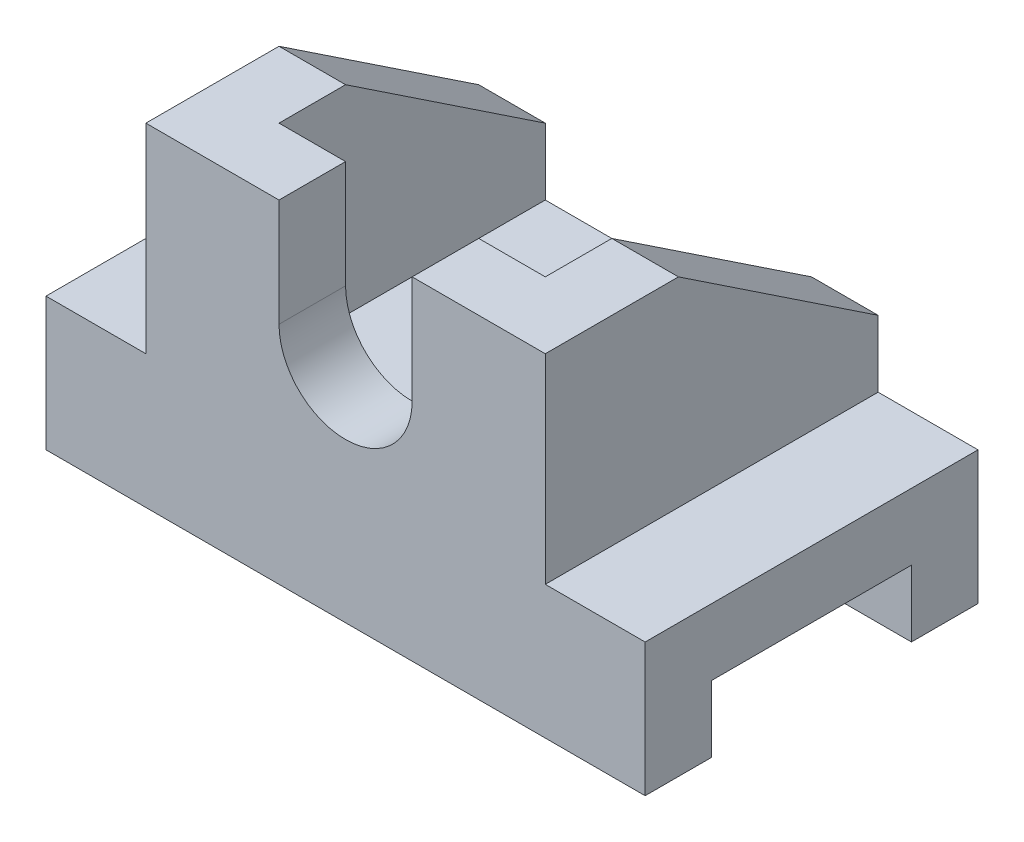
SolidWorks part; units mm, degrees
material "Nickel"
ref_plane "Front Plane" through (0, 0, 0) normal (0, 0, 1) x (1, 0, 0)
ref_plane "Top Plane" through (0, 0, 0) normal (0, 1, 0) x (1, 0, 0)
ref_plane "Right Plane" through (0, 0, 0) normal (1, 0, 0) x (0, 0, -1)
sketch "Sketch1" plane through (0, 0, 0) normal (1, 0, 0) x (0, 0, -1)
  line L0 (-14.6591, 0) -> (15.3409, 0)
  line L1 (15.3409, 0) -> (15.3409, -10)
  line L2 (15.3409, -10) -> (25.3409, -10)
  line L3 (25.3409, -10) -> (25.3409, 10)
  line L4 (25.3409, 10) -> (-24.6591, 10)
  line L5 (-24.6591, 10) -> (-24.6591, -10)
  line L6 (-24.6591, -10) -> (-14.6591, -10)
  line L7 (-14.6591, -10) -> (-14.6591, 0)
  dimension "D1" = 50
  dimension "D2" = 10
  dimension "D3" = 10
  dimension "D4" = 20
extrude "Boss-Extrude1" add sketch "Sketch1" along normal mid plane 90
sketch "Sketch2" plane through (0, 0, 24.6591) normal (0, 0, 1) x (1, 0, 0)
  line L0 (-30, 10) -> (-30, 40)
  line L1 (-30, 40) -> (30, 40)
  line L2 (30, 40) -> (30, 10)
  line L4 (-45, 10) -> (-45, -10)
  line L5 (-45, -10) -> (45, -10)
  line L6 (45, -10) -> (45, 10)
  line L7 (45, 10) -> (-45, 10)
  line L11 (30, 10) -> (-30, 10)
  point P6 (0, 10)
  dimension "D2" = 60
  dimension "D3" = 50
  dimension "D1" = 0
extrude "Boss-Extrude2" add sketch "Sketch2" against normal blind 10
sketch "Sketch3" plane through (0, 0, 24.6591) normal (0, 0, 1) x (1, 0, 0)
  line L0 (-10, 23.8342) -> (-10, 40)
  line L1 (30, 40) -> (-30, 40) construction
  line L2 (-10, 40) -> (10, 40)
  line L3 (10, 40) -> (10, 23.8342)
  arc A0 (-10, 23.8342) -> (10, 23.8342) centre (0, 23.8342) ccw
  dimension "D1" = 20
extrude "Cut-Extrude1" cut sketch "Sketch3" against normal through all
sketch "Sketch4" plane through (0, 10, 0) normal (0, 1, 0) x (1, 0, 0)
  line L0 (45, 25.3409) -> (-45, 25.3409) construction
  line L2 (-45, 25.3409) -> (-45, -24.6591) construction
  circle A0 centre (0, 5.3409) radius 10
  point P6 (-45, 5.73)
  dimension "D1" = 20
  dimension "D2" = 20
  dimension "D3" = 45
extrude "Cut-Extrude2" cut sketch "Sketch4" against normal blind 10
sketch "Sketch5" plane through (30, 0, 0) normal (1, 0, 0) x (0, 0, -1)
  line L0 (-14.6591, 10) -> (25.3409, 10)
  line L1 (25.3409, 10) -> (25.3409, 20)
  line L2 (25.3409, 20) -> (-4.6591, 40)
  line L3 (-4.6591, 40) -> (-14.6591, 40)
  line L4 (-24.6591, 40) -> (-24.6591, 10)
  line L5 (-24.6591, 10) -> (-14.6591, 10)
  line L6 (-14.6591, 10) -> (-14.6591, 40)
  line L7 (-14.6591, 40) -> (-24.6591, 40)
  line L10 (-14.6591, 10) -> (-14.6591, 40)
  point P4 (0, 0)
  dimension "D2" = 20
  dimension "D3" = 10
  dimension "D1" = 0
extrude "Boss-Extrude3" add sketch "Sketch5" against normal blind 10
mirror "Mirror1" about plane through (0, 0, 0) normal (1, 0, 0) of bodies 105
